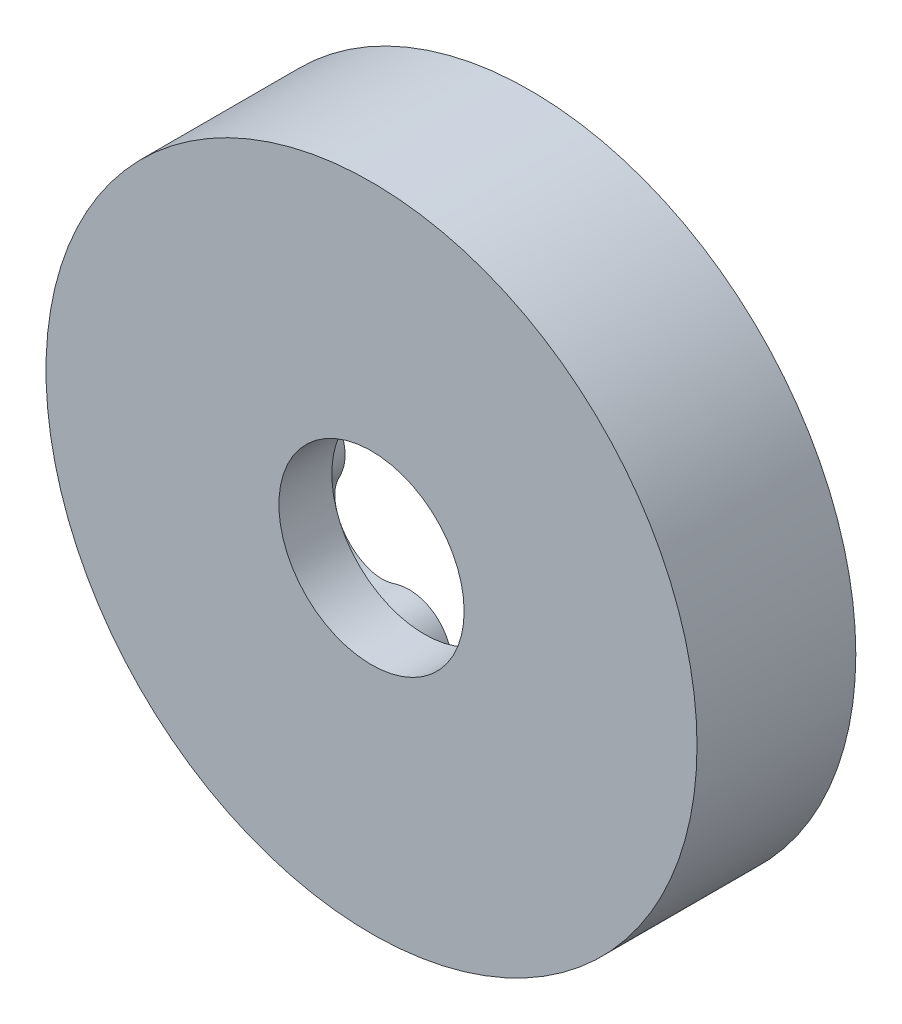
SolidWorks part; units mm, degrees
ref_plane "Plan de face" through (0, 0, 0) normal (0, 0, 1) x (1, 0, 0)
ref_plane "Plan de dessus" through (0, 0, 0) normal (0, 1, 0) x (1, 0, 0)
ref_plane "Plan de droite" through (0, 0, 0) normal (1, 0, 0) x (0, 0, -1)
sketch "Esquisse1" plane through (0, 0, 0) normal (0, 0, 1) x (1, 0, 0)
  line L0 (-1000, 0) -> (49000, 0) construction
  circle A1 centre (0, 0) radius 12.3
  spline S0 degree 4 poles (8.5765, 1.9975) (8.5522, 1.8955) (8.5001, 1.74) (8.4135, 1.5639) (8.2721, 1.3901) (8.1598, 1.2805) (8.0623, 1.1864) (7.9638, 1.0813) (7.8683, 0.9623) (7.7905, 0.8464) (7.7165, 0.7143) (7.6601, 0.5877) (7.6187, 0.4695) (7.5874, 0.3477) (7.5685, 0.2503) (7.5558, 0.1518) (7.5494, 0.0362) (7.5495, -0.0377) (7.556, -0.1549) (7.5692, -0.2548) (7.5928, -0.3744) (7.6318, -0.5134) (7.6996, -0.6862) (7.8097, -0.8864) (7.9383, -1.0561) (8.0744, -1.1995) (8.2139, -1.3311) (8.3635, -1.4895) (8.5212, -1.7603) (8.6228, -2.1212) (8.64, -2.5254) (8.5726, -2.9252) (8.4432, -3.2787) (8.2368, -3.6263) (7.9593, -3.926) (7.6441, -4.137) (7.3443, -4.241) (7.1185, -4.2618) (6.9234, -4.274) (6.7295, -4.2994) (6.479, -4.3613) (6.1856, -4.4928) (5.901, -4.7013) (5.6546, -4.995) (5.4986, -5.3114) (5.4201, -5.6233) (5.4027, -5.8807) (5.4113, -6.076) (5.4331, -6.2703) (5.4519, -6.4963) (5.4016, -6.8096) (5.2485, -7.1567) (5.0015, -7.482) (4.6932, -7.7473) (4.3627, -7.938) (3.9788, -8.0724) (3.5736, -8.1236) (3.1965, -8.0827) (2.9, -7.9696) (2.7137, -7.8404) (2.5563, -7.7244) (2.3915, -7.6192) (2.1598, -7.5056) (1.8505, -7.4177) (1.4985, -7.3945) (1.121, -7.4611) (0.7981, -7.6033) (0.5375, -7.7917) (0.3587, -7.9776) (0.2397, -8.1329) (0.1315, -8.2957) (0.0006, -8.4809) (-0.2393, -8.6885) (-0.5796, -8.856) (-0.9779, -8.9464) (-1.3847, -8.9514) (-1.7604, -8.8852) (-2.1409, -8.7414) (-2.4842, -8.5201) (-2.7468, -8.2464) (-2.9012, -7.9692) (-2.9609, -7.7504) (-3.0069, -7.5604) (-3.0656, -7.3738) (-3.17, -7.1379) (-3.3504, -6.8718) (-3.6052, -6.6277) (-3.9372, -6.4361) (-4.2759, -6.3374) (-4.5966, -6.3143) (-4.8532, -6.3418) (-5.0441, -6.3842) (-5.2316, -6.4394) (-5.4509, -6.4971) (-5.7682, -6.502) (-6.1365, -6.4115) (-6.4998, -6.2248) (-6.8146, -5.9672) (-7.0598, -5.6749) (-7.2589, -5.3201) (-7.3797, -4.93) (-7.4049, -4.5515) (-7.345, -4.2399) (-7.25, -4.0339) (-7.1631, -3.8588) (-7.0882, -3.6782) (-7.0165, -3.4303) (-6.9837, -3.1106) (-7.0229, -2.7501) (-7.1639, -2.3731) (-7.3888, -2.0525) (-7.6749, -1.8049) (-7.9618, -1.6436) (-8.2238, -1.5439) (-8.4343, -1.4082) (-8.5926, -1.2582) (-8.7221, -1.0955) (-8.8246, -0.9284) (-8.9063, -0.7535) (-8.9682, -0.5843) (-9.0116, -0.4021) (-9.0385, -0.2534) (-9.0499, -0.0695) (-9.0511, 0.0228) (-9.0456, 0.145) (-9.0361, 0.2474) (-9.0218, 0.3429) (-9.0027, 0.4392) (-8.9728, 0.5589) (-8.924, 0.71) (-8.8469, 0.8892) (-8.7354, 1.0787) (-8.599, 1.2513) (-8.4564, 1.3861) (-8.3155, 1.4863) (-8.1727, 1.5588) (-8.0371, 1.617) (-7.9373, 1.6649) (-7.8723, 1.6997) (-7.8401, 1.7178) knots 0 0 0 0 0 0.01184 0.018557 0.021916 0.025274 0.029587 0.033899 0.038212 0.042525 0.04536 0.05103 0.053865 0.0567 0.059534 0.062369 0.065203 0.068091 0.070978 0.073865 0.076752 0.081992 0.087231 0.094866 0.102501 0.106028 0.109555 0.116608 0.127054 0.141093 0.151538 0.161983 0.172711 0.18344 0.19705 0.207783 0.215196 0.218902 0.222608 0.229945 0.237282 0.248012 0.258762 0.269512 0.280242 0.287579 0.294915 0.298622 0.302328 0.30974 0.320474 0.334084 0.344812 0.355541 0.36627 0.376999 0.390609 0.401342 0.408755 0.412461 0.416167 0.423504 0.430841 0.44157 0.452321 0.463071 0.4738 0.481137 0.488474 0.49218 0.495887 0.503299 0.514032 0.527642 0.538371 0.5491 0.559829 0.570557 0.584167 0.594901 0.602313 0.606019 0.609726 0.617062 0.624399 0.635129 0.645879 0.656629 0.667359 0.674696 0.682033 0.685739 0.689445 0.696858 0.707591 0.721201 0.73193 0.742658 0.753387 0.764116 0.777726 0.788459 0.795872 0.799578 0.803284 0.810621 0.817958 0.828687 0.839438 0.851255 0.863061 0.872486 0.881911 0.888313 0.894714 0.900613 0.906512 0.911736 0.916961 0.922186 0.92741 0.931814 0.936217 0.939001 0.941785 0.94457 0.947354 0.950138 0.952922 0.958491 0.965327 0.972162 0.977732 0.983302 0.987477 0.991651 0.995826 1 1 1 1 1 construction
  spline S1 degree 4 poles (7.55, 0) (7.55, -0.0222) (7.5511, -0.0666) (7.556, -0.1549) (7.5692, -0.2548) (7.5928, -0.3744) (7.6318, -0.5134) (7.6996, -0.6862) (7.8097, -0.8864) (7.9383, -1.0561) (8.0744, -1.1995) (8.2139, -1.3311) (8.3635, -1.4895) (8.5212, -1.7603) (8.6228, -2.1212) (8.64, -2.5254) (8.5726, -2.9252) (8.4432, -3.2787) (8.2368, -3.6263) (7.9593, -3.926) (7.6441, -4.137) (7.3443, -4.241) (7.1185, -4.2618) (6.9234, -4.274) (6.7295, -4.2994) (6.479, -4.3613) (6.1856, -4.4928) (5.901, -4.7013) (5.6546, -4.995) (5.4986, -5.3114) (5.4201, -5.6233) (5.4027, -5.8807) (5.4113, -6.076) (5.4331, -6.2703) (5.4519, -6.4963) (5.4016, -6.8096) (5.2485, -7.1567) (5.0015, -7.482) (4.6932, -7.7473) (4.3627, -7.938) (3.9788, -8.0724) (3.5736, -8.1236) (3.1965, -8.0827) (2.9, -7.9696) (2.7137, -7.8404) (2.5563, -7.7244) (2.3915, -7.6192) (2.1598, -7.5056) (1.8505, -7.4177) (1.4985, -7.3945) (1.121, -7.4611) (0.7981, -7.6033) (0.5375, -7.7917) (0.3587, -7.9776) (0.2397, -8.1329) (0.1315, -8.2957) (0.0006, -8.4809) (-0.2393, -8.6885) (-0.5796, -8.856) (-0.9779, -8.9464) (-1.3847, -8.9514) (-1.7604, -8.8852) (-2.1409, -8.7414) (-2.4842, -8.5201) (-2.7468, -8.2464) (-2.9012, -7.9692) (-2.9609, -7.7504) (-3.0069, -7.5604) (-3.0656, -7.3738) (-3.17, -7.1379) (-3.3504, -6.8718) (-3.6052, -6.6277) (-3.9372, -6.4361) (-4.2759, -6.3374) (-4.5966, -6.3143) (-4.8532, -6.3418) (-5.0441, -6.3842) (-5.2316, -6.4394) (-5.4509, -6.4971) (-5.7682, -6.502) (-6.1365, -6.4115) (-6.4998, -6.2248) (-6.8146, -5.9672) (-7.0598, -5.6749) (-7.2589, -5.3201) (-7.3797, -4.93) (-7.4049, -4.5515) (-7.345, -4.2399) (-7.25, -4.0339) (-7.1631, -3.8588) (-7.0882, -3.6782) (-7.0165, -3.4303) (-6.9837, -3.1106) (-7.0229, -2.7501) (-7.1639, -2.3731) (-7.3888, -2.0525) (-7.6749, -1.8049) (-7.9618, -1.6436) (-8.2238, -1.5439) (-8.4343, -1.4082) (-8.5926, -1.2582) (-8.7221, -1.0955) (-8.8246, -0.9284) (-8.9063, -0.7535) (-8.9682, -0.5843) (-9.0116, -0.4021) (-9.0385, -0.2534) (-9.048, -0.1) (-9.05, -0.0339) (-9.05, 0) knots 0.065203 0.065203 0.065203 0.065203 0.065203 0.068091 0.070978 0.073865 0.076752 0.081992 0.087231 0.094866 0.102501 0.106028 0.109555 0.116608 0.127054 0.141093 0.151538 0.161983 0.172711 0.18344 0.19705 0.207783 0.215196 0.218902 0.222608 0.229945 0.237282 0.248012 0.258762 0.269512 0.280242 0.287579 0.294915 0.298622 0.302328 0.30974 0.320474 0.334084 0.344812 0.355541 0.36627 0.376999 0.390609 0.401342 0.408755 0.412461 0.416167 0.423504 0.430841 0.44157 0.452321 0.463071 0.4738 0.481137 0.488474 0.49218 0.495887 0.503299 0.514032 0.527642 0.538371 0.5491 0.559829 0.570557 0.584167 0.594901 0.602313 0.606019 0.609726 0.617062 0.624399 0.635129 0.645879 0.656629 0.667359 0.674696 0.682033 0.685739 0.689445 0.696858 0.707591 0.721201 0.73193 0.742658 0.753387 0.764116 0.777726 0.788459 0.795872 0.799578 0.803284 0.810621 0.817958 0.828687 0.839438 0.851255 0.863061 0.872486 0.881911 0.888313 0.894714 0.900613 0.906512 0.911736 0.916961 0.922186 0.92741 0.931814 0.936217 0.936217 0.936217 0.936217 0.936217
  spline S2 degree 4 poles (7.55, 0) (7.55, 0.0222) (7.5511, 0.0666) (7.556, 0.1549) (7.5692, 0.2548) (7.5928, 0.3744) (7.6318, 0.5134) (7.6996, 0.6862) (7.8097, 0.8864) (7.9383, 1.0561) (8.0744, 1.1995) (8.2139, 1.3311) (8.3635, 1.4895) (8.5212, 1.7603) (8.6228, 2.1212) (8.64, 2.5254) (8.5726, 2.9252) (8.4432, 3.2787) (8.2368, 3.6263) (7.9593, 3.926) (7.6441, 4.137) (7.3443, 4.241) (7.1185, 4.2618) (6.9234, 4.274) (6.7295, 4.2994) (6.479, 4.3613) (6.1856, 4.4928) (5.901, 4.7013) (5.6546, 4.995) (5.4986, 5.3114) (5.4201, 5.6233) (5.4027, 5.8807) (5.4113, 6.076) (5.4331, 6.2703) (5.4519, 6.4963) (5.4016, 6.8096) (5.2485, 7.1567) (5.0015, 7.482) (4.6932, 7.7473) (4.3627, 7.938) (3.9788, 8.0724) (3.5736, 8.1236) (3.1965, 8.0827) (2.9, 7.9696) (2.7137, 7.8404) (2.5563, 7.7244) (2.3915, 7.6192) (2.1598, 7.5056) (1.8505, 7.4177) (1.4985, 7.3945) (1.121, 7.4611) (0.7981, 7.6033) (0.5375, 7.7917) (0.3587, 7.9776) (0.2397, 8.1329) (0.1315, 8.2957) (0.0006, 8.4809) (-0.2393, 8.6885) (-0.5796, 8.856) (-0.9779, 8.9464) (-1.3847, 8.9514) (-1.7604, 8.8852) (-2.1409, 8.7414) (-2.4842, 8.5201) (-2.7468, 8.2464) (-2.9012, 7.9692) (-2.9609, 7.7504) (-3.0069, 7.5604) (-3.0656, 7.3738) (-3.17, 7.1379) (-3.3504, 6.8718) (-3.6052, 6.6277) (-3.9372, 6.4361) (-4.2759, 6.3374) (-4.5966, 6.3143) (-4.8532, 6.3418) (-5.0441, 6.3842) (-5.2316, 6.4394) (-5.4509, 6.4971) (-5.7682, 6.502) (-6.1365, 6.4115) (-6.4998, 6.2248) (-6.8146, 5.9672) (-7.0598, 5.6749) (-7.2589, 5.3201) (-7.3797, 4.93) (-7.4049, 4.5515) (-7.345, 4.2399) (-7.25, 4.0339) (-7.1631, 3.8588) (-7.0882, 3.6782) (-7.0165, 3.4303) (-6.9837, 3.1106) (-7.0229, 2.7501) (-7.1639, 2.3731) (-7.3888, 2.0525) (-7.6749, 1.8049) (-7.9618, 1.6436) (-8.2238, 1.5439) (-8.4343, 1.4082) (-8.5926, 1.2582) (-8.7221, 1.0955) (-8.8246, 0.9284) (-8.9063, 0.7535) (-8.9682, 0.5843) (-9.0116, 0.4021) (-9.0385, 0.2534) (-9.048, 0.1) (-9.05, 0.0339) (-9.05, 0) knots 0.065203 0.065203 0.065203 0.065203 0.065203 0.068091 0.070978 0.073865 0.076752 0.081992 0.087231 0.094866 0.102501 0.106028 0.109555 0.116608 0.127054 0.141093 0.151538 0.161983 0.172711 0.18344 0.19705 0.207783 0.215196 0.218902 0.222608 0.229945 0.237282 0.248012 0.258762 0.269512 0.280242 0.287579 0.294915 0.298622 0.302328 0.30974 0.320474 0.334084 0.344812 0.355541 0.36627 0.376999 0.390609 0.401342 0.408755 0.412461 0.416167 0.423504 0.430841 0.44157 0.452321 0.463071 0.4738 0.481137 0.488474 0.49218 0.495887 0.503299 0.514032 0.527642 0.538371 0.5491 0.559829 0.570557 0.584167 0.594901 0.602313 0.606019 0.609726 0.617062 0.624399 0.635129 0.645879 0.656629 0.667359 0.674696 0.682033 0.685739 0.689445 0.696858 0.707591 0.721201 0.73193 0.742658 0.753387 0.764116 0.777726 0.788459 0.795872 0.799578 0.803284 0.810621 0.817958 0.828687 0.839438 0.851255 0.863061 0.872486 0.881911 0.888313 0.894714 0.900613 0.906512 0.911736 0.916961 0.922186 0.92741 0.931814 0.936217 0.936217 0.936217 0.936217 0.936217
  dimension "D1" = 24.6
extrude "Boss.-Extru.4" add sketch "Esquisse1" along normal blind 4
sketch "Esquisse2" plane through (0, 0, 4) normal (0, 0, 1) x (1, 0, 0)
  circle A0 centre (0, 0) radius 12.3
  circle A1 centre (0, 0) radius 3.5
  dimension "D1" = 7
extrude "Boss.-Extru.5" add sketch "Esquisse2" along normal blind 2
equation "\"R\"= 9.8'Radius of the rotor"
equation "\"E\"= 0.75'Eccentricity from input shaft to center of rotor"
equation "\"Rr\"= 1.5'Roller radius"
equation "\"N\"= 10'Amount of rollers"
